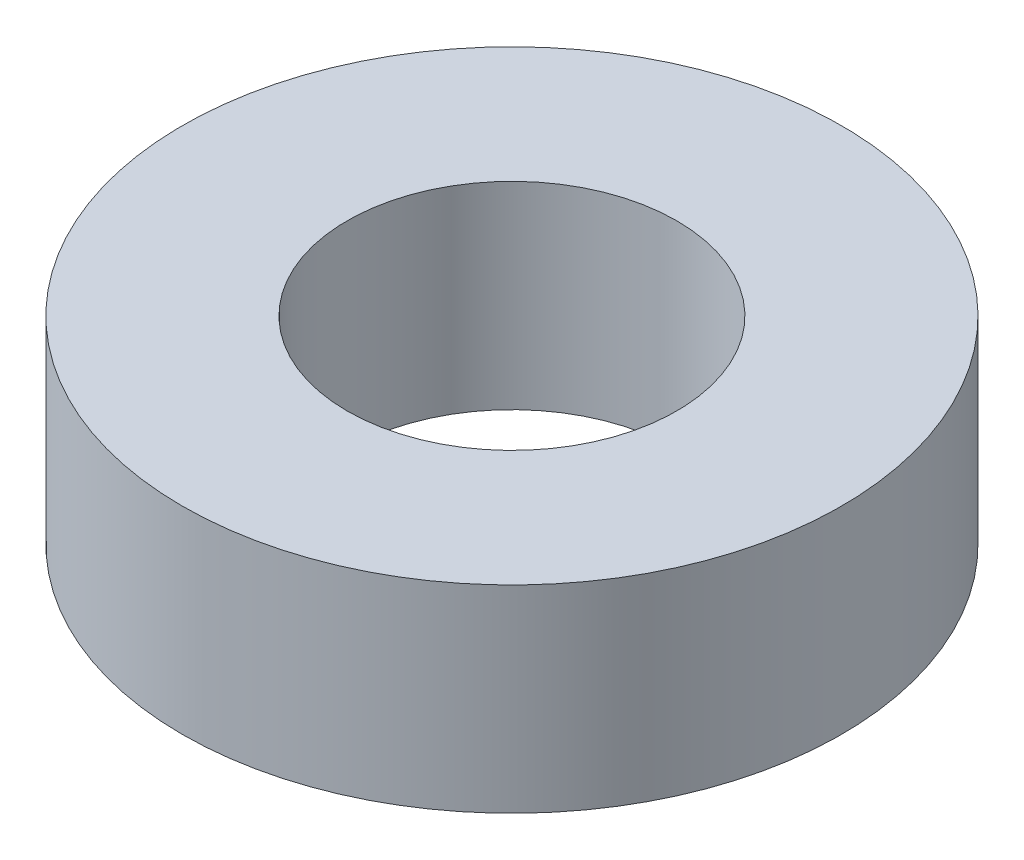
SolidWorks part; units mm, degrees
material "聚脂树脂"
ref_plane "前视基准面" through (0, 0, 0) normal (0, 0, 1) x (1, 0, 0)
ref_plane "上视基准面" through (0, 0, 0) normal (0, 1, 0) x (1, 0, 0)
ref_plane "右视基准面" through (0, 0, 0) normal (1, 0, 0) x (0, 0, -1)
other "Configuration Table"
sketch "草图1" plane through (0, 0, 0) normal (0, 1, 0) x (1, 0, 0)
  circle A0 centre (0, 0) radius 2.5
  circle A1 centre (0, 0) radius 5
  dimension "D1" = 5
  dimension "D2" = 10
extrude "凸台-拉伸1" add sketch "草图1" along normal blind 3
